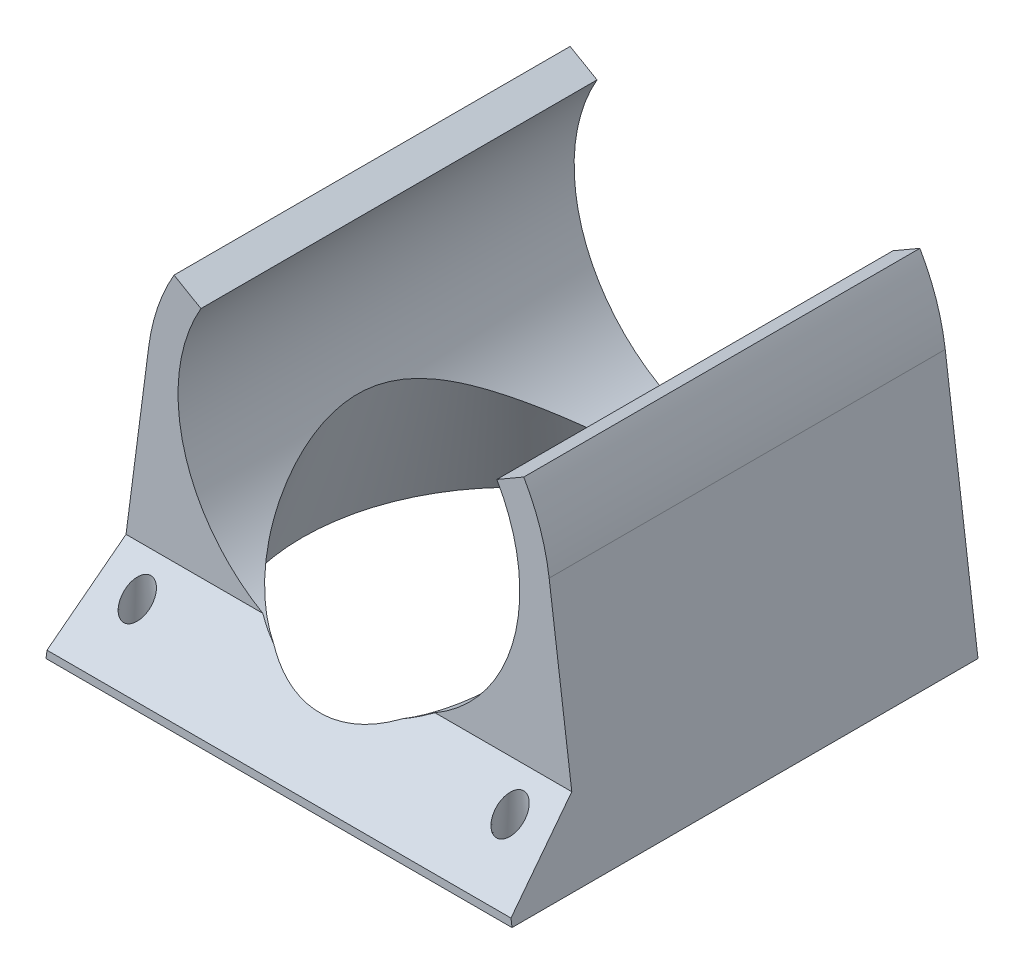
SolidWorks part; units mm, degrees
ref_plane "前视" through (0, 0, 0) normal (0, 0, 1) x (1, 0, 0)
ref_plane "上视" through (0, 0, 0) normal (0, 1, 0) x (1, 0, 0)
ref_plane "右视" through (0, 0, 0) normal (1, 0, 0) x (0, 0, -1)
sketch "草图1" plane through (0, 0, 0) normal (0, 0, 1) x (1, 0, 0)
  line L0 (-9.5263, 5.5) -> (-11.2583, 6.5)
  line L1 (-12.891, 1.6803) -> (-15, -14.5)
  line L2 (11.2583, 6.5) -> (9.5263, 5.5)
  line L3 (0, 0) -> (0, 23.1119) construction
  line L4 (-15, -14.5) -> (15, -14.5)
  line L5 (15, -14.5) -> (12.891, 1.6803)
  arc A0 (-9.5263, 5.5) -> (9.5263, 5.5) centre (0, 0) ccw
  arc A1 (-11.2583, 6.5) -> (-12.891, 1.6803) centre (0, 0) ccw
  arc A2 (12.891, 1.6803) -> (11.2583, 6.5) centre (0, 0) ccw
  point P10 (0, -14.5)
  dimension "D1" = 22
  dimension "D4" = 13
  dimension "D2" = 120
  dimension "D3" = 60
  dimension "D5" = 14.5
  dimension "D6" = 30
extrude "凸台-拉伸1" add sketch "草图1" along normal blind 30
sketch "草图2" plane through (0, 0, 0) normal (1, 0, 0) x (0, 0, -1)
  line L0 (-30, -14) -> (-25.5, -9.5)
  line L1 (-30, -14.5) -> (-30, 1.6803) construction
  line L2 (-25.5, -9.5) -> (-25.5, 7.3594)
  line L3 (-25.5, 7.3594) -> (-30, 7.3594)
  line L4 (-30, 7.3594) -> (-30, -14)
  line L5 (-30, 1.6803) -> (-30, -14.5) construction
  line L6 (-30, -14.5) -> (0, -14.5) construction
  dimension "D1" = 4.5
  dimension "D2" = 4.5
  dimension "D3" = 0.5
extrude "切除-拉伸1" cut sketch "草图2" against normal mid plane 50
sketch "草图3" plane through (0, -14.5, 0) normal (0, -1, 0) x (1, 0, 0)
  line L0 (-15, 0) -> (15, 0) construction
  circle A0 centre (0, 15) radius 13.5
  dimension "D1" = 27
  dimension "D2" = 15
extrude "切除-拉伸2" cut sketch "草图3" against normal blind 50 draft 20
sketch "草图4" plane through (0, -14.5, 0) normal (0, -1, 0) x (1, 0, 0)
  line L1 (12, 3) -> (-12, 3) construction
  line L2 (12, 3) -> (12, 27) construction
  line L3 (12, 27) -> (-12, 27) construction
  line L4 (-12, 3) -> (-12, 27) construction
  line L5 (12, 3) -> (-12, 27) construction
  line L6 (12, 27) -> (-12, 3) construction
  circle A0 centre (-12, 27) radius 1.35
  circle A1 centre (12, 27) radius 1.35
  circle A2 centre (-12, 3) radius 1.35
  circle A3 centre (12, 3) radius 1.35
  point P0 (0, 15)
  dimension "D2" = 2.7
  dimension "D1" = 24
extrude "切除-拉伸3" cut sketch "草图4" against normal blind 8 draft 8
